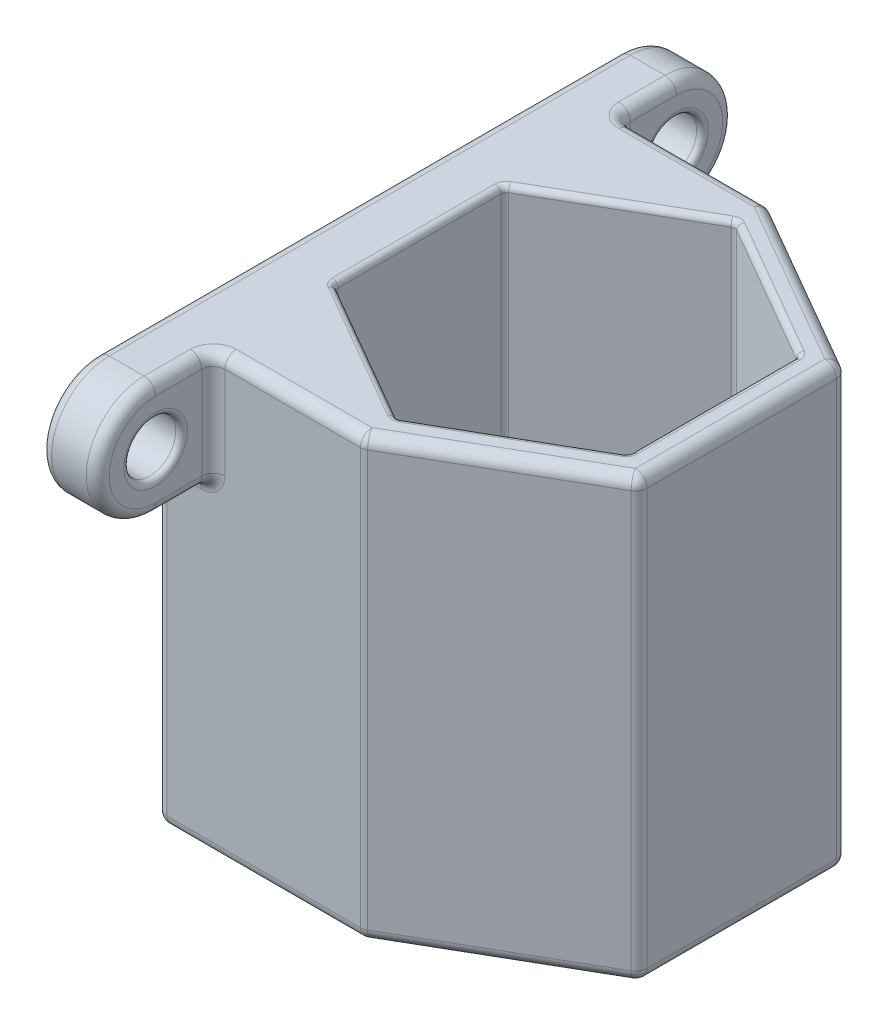
SolidWorks part; units mm, degrees
ref_plane "Front Plane" through (0, 0, 0) normal (0, 0, 1) x (1, 0, 0)
ref_plane "Top Plane" through (0, 0, 0) normal (0, 1, 0) x (1, 0, 0)
ref_plane "Right Plane" through (0, 0, 0) normal (1, 0, 0) x (0, 0, -1)
sketch "Sketch1" plane through (0, 0, 0) normal (0, 1, 0) x (1, 0, 0)
  line L0 (0, -14.6647) -> (0, 0) construction
  line L5 (0, -14.6647) -> (12.7, -7.3323)
  line L6 (12.7, -7.3323) -> (12.7, 7.3323)
  line L7 (12.7, 7.3323) -> (0, 14.6647)
  line L8 (0, 14.6647) -> (-12.7, 7.3323)
  line L9 (-12.7, 7.3323) -> (-12.7, -7.3323)
  line L10 (-12.7, -7.3323) -> (0, -14.6647)
  line L11 (0, -17.5514) -> (0, -14.6647) construction
  line L12 (15.2, -8.7757) -> (15.2, 8.7757)
  line L13 (15.2, 8.7757) -> (0, 17.5514)
  line L14 (0, 17.5514) -> (-15.2, 8.7757)
  line L15 (-15.2, 8.7757) -> (-15.2, -8.7757)
  line L16 (-15.2, -8.7757) -> (0, -17.5514)
  line L17 (0, -17.5514) -> (15.2, -8.7757)
  circle A0 centre (0, 0) radius 12.7 construction
  circle A1 centre (0, 0) radius 15.2 construction
  dimension "D1" = 25.4
  dimension "D2" = 2.5
extrude "Boss-Extrude1" add sketch "Sketch1" along normal blind 25
sketch "Sketch2" plane through (0, 0, 0) normal (0, -1, 0) x (1, 0, 0)
  line L1 (0, -17.5514) -> (15.2, -8.7757)
  line L2 (15.2, -8.7757) -> (15.2, 8.7757)
  line L3 (15.2, 8.7757) -> (0, 17.5514)
  line L4 (0, 17.5514) -> (-15.2, 8.7757)
  line L5 (-15.2, 8.7757) -> (-15.2, -8.7757)
  line L6 (-15.2, -8.7757) -> (0, -17.5514)
  circle A0 centre (0, 0) radius 15.2 construction
  point P1 (0, -17.5514)
extrude "Boss-Extrude2" add sketch "Sketch2" along normal blind 2.5
sketch "Sketch3" plane through (0, -2.5, 0) normal (0, -1, 0) x (1, 0, 0)
  line L0 (0, 0) -> (0, -5.7735) construction
  line L1 (0, -5.7735) -> (5, -2.8868)
  line L2 (5, -2.8868) -> (5, 2.8868)
  line L3 (5, 2.8868) -> (0, 5.7735)
  line L4 (0, 5.7735) -> (-5, 2.8868)
  line L5 (-5, 2.8868) -> (-5, -2.8868)
  line L6 (-5, -2.8868) -> (0, -5.7735)
  line L7 (0, -17.5514) -> (15.2, -8.7757)
  line L8 (15.2, -8.7757) -> (15.2, 8.7757)
  line L9 (15.2, 8.7757) -> (0, 17.5514)
  line L10 (0, 17.5514) -> (-15.2, 8.7757)
  line L11 (-15.2, 8.7757) -> (-15.2, -8.7757)
  line L12 (-15.2, -8.7757) -> (0, -17.5514)
  circle A0 centre (0, 0) radius 5 construction
  circle A1 centre (0, 0) radius 15.2 construction
  dimension "D1" = 10
extrude "Boss-Extrude3" add sketch "Sketch3" along normal blind 8
sketch "Sketch4" plane through (0, -10.5, 0) normal (0, -1, 0) x (1, 0, 0)
  line L1 (0, -17.5514) -> (15.2, -8.7757)
  line L2 (15.2, -8.7757) -> (15.2, 8.7757)
  line L3 (15.2, 8.7757) -> (0, 17.5514)
  line L4 (0, 17.5514) -> (-15.2, 8.7757)
  line L5 (-15.2, 8.7757) -> (-15.2, -8.7757)
  line L6 (-15.2, -8.7757) -> (0, -17.5514)
  circle A0 centre (0, 0) radius 15.2 construction
  point P1 (0, -17.5514)
extrude "Boss-Extrude4" add sketch "Sketch4" along normal blind 2.5
sketch "Sketch5" plane through (0, -13, 0) normal (0, -1, 0) x (1, 0, 0)
  circle A0 centre (0, 0) radius 3.25
  dimension "D1" = 6.5
extrude "Cut-Extrude1" cut sketch "Sketch5" against normal through all
sketch "Sketch6" plane through (0, -13, 0) normal (0, -1, 0) x (1, 0, 0)
  line L0 (0, 17.5514) -> (-18, 17.5514)
  line L1 (-18, 17.5514) -> (-18, -17.5514)
  line L2 (-18, -17.5514) -> (0, -17.5514)
  line L3 (0, 17.5514) -> (-15.2, 8.7757)
  line L4 (-15.2, 8.7757) -> (-15.2, -8.7757)
  line L5 (-15.2, -8.7757) -> (0, -17.5514)
  dimension "D1" = 2.8
extrude "Boss-Extrude5" add sketch "Sketch6" against normal up to surface (38 mm away) up to face at (0, 25, 0)
sketch "Sketch7" plane through (-18, 0, 0) normal (-1, 0, 0) x (0, 0, 1)
  line L0 (-22.5514, 25) -> (22.5514, 25)
  line L1 (-22.5514, 15) -> (22.5514, 15)
  line L2 (0, 0) -> (0, 15) construction
  line L3 (17.5514, 25) -> (-17.5514, 25) construction
  line L4 (-17.5514, 25) -> (-17.5514, -13) construction
  circle A0 centre (-22.5514, 20) radius 5
  circle A1 centre (22.5514, 20) radius 5
  circle A2 centre (22.5514, 20) radius 2.25
  circle A3 centre (-22.5514, 20) radius 2.25
  line M8 (17.5514, -13) -> (17.5514, 25)
  line M10 (-17.5514, 25) -> (-17.5514, -13)
  dimension "D1" = 4.5
  dimension "D2" = 2.75
extrude "Boss-Extrude6" add sketch "Sketch7" against normal blind 5 contours A0 L0 M10 | A0 L1 M10 | A0 A3 | A1 A2 | A1 L1 M8 | A1 L0 M8
sketch "Sketch8" plane through (0, -2.5, 0) normal (0, -1, 0) x (1, 0, 0)
  circle A0 centre (0, 0) radius 3.25
  circle A1 centre (0, 0) radius 3.25 construction
extrude "Boss-Extrude7" add sketch "Sketch8" against normal blind 0.2
fillet "Fillet1" radius 0.5 19 edges at (0, 0, -3.25) (12.7, 25, 0) (12.7, 0, 0) (6.35, 25, -10.9985) (12.7, 12.5, -7.3323) (6.35, 0, -10.9985) (12.7, 12.5, 7.3323) (6.35, 25, 10.9985) (6.35, 0, 10.9985) (0, 12.5, 14.6647) (-6.35, 25, 10.9985) (-6.35, 0, 10.9985) (-12.7, 12.5, 7.3323) (-12.7, 25, 0) (-12.7, 0, 0) (-12.7, 12.5, -7.3323) (-6.35, 25, -10.9985) (0, 12.5, -14.6647) (-6.35, 0, -10.9985)
fillet "Fillet2" radius 1 32 edges at (-18, 15, 20.0514) (-13, 15, 20.0514) (-13, 25, 20.0514) (-13, 25, -20.0514) (-18, 15, -20.0514) (-13, 15, -20.0514) (-18, 20, -27.5514) (-13, 20, -27.5514) (-18, 1, -17.5514) (-9, -13, -17.5514) (-6.5, 25, -17.5514) (-13, 20, -17.5514) (-15.5, 15, -17.5514) (7.6, -13, -13.1636) (7.6, 25, -13.1636) (0, 6, -17.5514) (-9, -13, 17.5514) (-6.5, 25, 17.5514) (-18, 1, 17.5514) (-15.5, 15, 17.5514) (-13, 20, 17.5514) (15.2, -13, 0) (15.2, 25, 0) (15.2, 6, -8.7757) (7.6, -13, 13.1636) (7.6, 25, 13.1636) (15.2, 6, 8.7757) (0, 6, 17.5514) (-18, 20, 27.5514) (-13, 20, 27.5514) (-18, -13, 0) (-18, 25, 0)
fillet "Fillet3" radius 0.5 6 edges at (-18, 20, -20.3014) (-13, 20, -20.3014) (-18, 20, 24.8014) (-13, 20, 24.8014) (0, -10.5, -3.25) (0, -13, -3.25)
